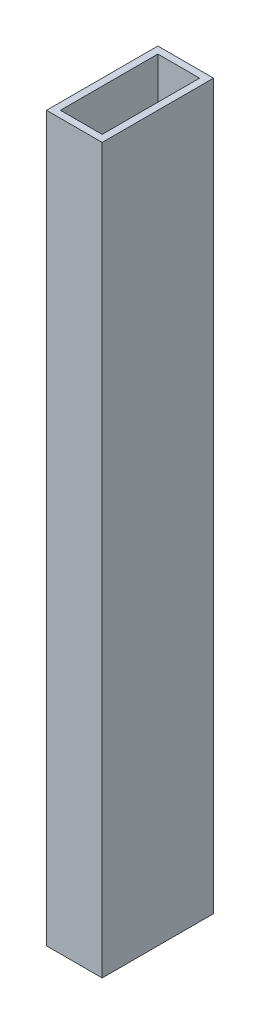
SolidWorks part; units mm, degrees
ref_plane "Front Plane" through (0, 0, 0) normal (0, 0, 1) x (1, 0, 0)
ref_plane "Top Plane" through (0, 0, 0) normal (0, 1, 0) x (1, 0, 0)
ref_plane "Right Plane" through (0, 0, 0) normal (1, 0, 0) x (0, 0, -1)
sketch "Sketch1" plane through (0, 0, 0) normal (0, 1, 0) x (1, 0, 0)
  line L0 (-9.525, 22.225) -> (9.525, 22.225)
  line L1 (-12.7, -25.4) -> (12.7, -25.4)
  line L2 (-12.7, -25.4) -> (-12.7, 25.4)
  line L3 (-12.7, 25.4) -> (12.7, 25.4)
  line L4 (12.7, -25.4) -> (12.7, 25.4)
  line L5 (-12.7, -25.4) -> (12.7, 25.4) construction
  line L6 (-12.7, 25.4) -> (12.7, -25.4) construction
  line L7 (9.525, -22.225) -> (9.525, 22.225)
  line L8 (-9.525, -22.225) -> (9.525, -22.225)
  line L9 (-9.525, -22.225) -> (-9.525, 22.225)
  point P0 (0, 0)
  dimension "D1" = 25.4
  dimension "D2" = 50.8
  dimension "D3" = 3.175
extrude "Boss-Extrude1" add sketch "Sketch1" along normal blind 330.2
